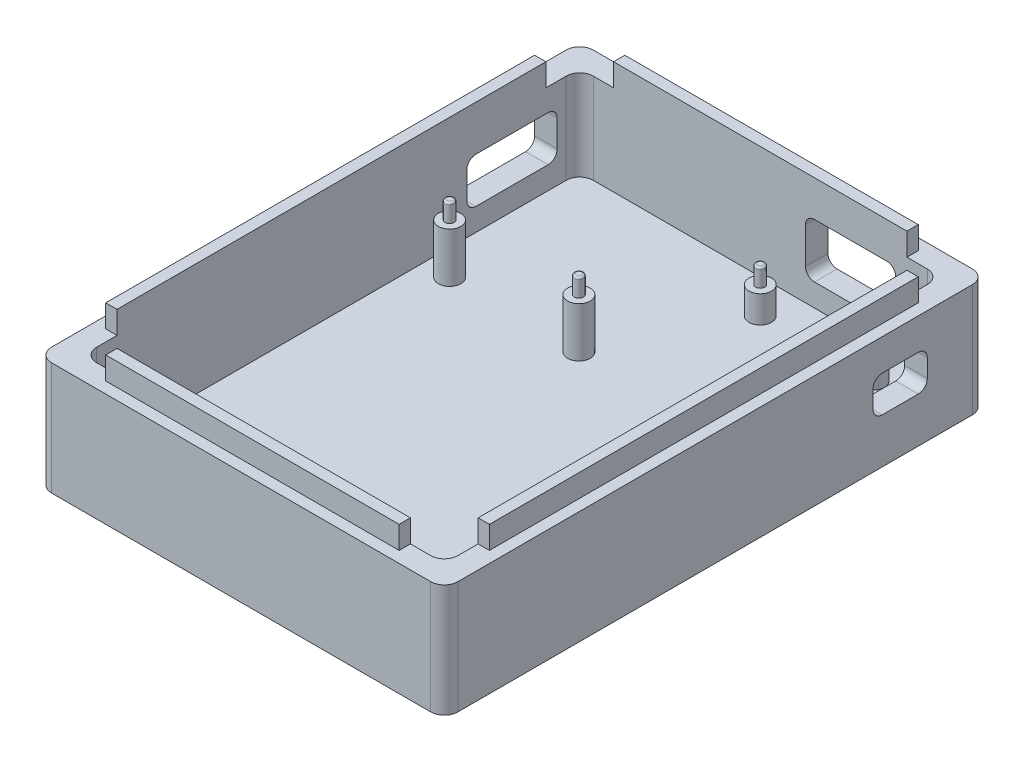
SolidWorks part; units mm, degrees
ref_plane "Alzado" through (0, 0, 0) normal (0, 0, 1) x (1, 0, 0)
ref_plane "Planta" through (0, 0, 0) normal (0, 1, 0) x (1, 0, 0)
ref_plane "Vista lateral" through (0, 0, 0) normal (1, 0, 0) x (0, 0, -1)
sketch "Croquis1" plane through (0, 0, 0) normal (0, 1, 0) x (1, 0, 0)
  line L1 (45, -60) -> (-45, -60)
  line L2 (45, -60) -> (45, 60)
  line L3 (45, 60) -> (-45, 60)
  line L4 (-45, -60) -> (-45, 60)
  line L5 (45, -60) -> (-45, 60) construction
  line L6 (45, 60) -> (-45, -60) construction
  point P0 (0, 0)
  dimension "D1" = 90
  dimension "D2" = 120
extrude "Saliente-Extruir1" add sketch "Croquis1" along normal blind 30
sketch "Croquis2" plane through (0, 30, 0) normal (0, 1, 0) x (1, 0, 0)
  line L0 (-45, 60) -> (-45, -60) construction
  line L1 (40, -55) -> (-40, -55)
  line L2 (40, -55) -> (40, 55)
  line L3 (40, 55) -> (-40, 55)
  line L4 (-40, -55) -> (-40, 55)
  line L5 (40, -55) -> (-40, 55) construction
  line L6 (40, 55) -> (-40, -55) construction
  line L7 (45, 60) -> (-45, 60) construction
  point P0 (0, 0)
  dimension "D1" = 5
  dimension "D2" = 5
extrude "Cortar-Extruir1" cut sketch "Croquis2" against normal blind 25
sketch "Croquis3" plane through (0, 30, 0) normal (0, 1, 0) x (1, 0, 0)
  line L1 (45, -60) -> (-45, -60)
  line L2 (45, -60) -> (45, 60)
  line L3 (45, 60) -> (-45, 60)
  line L4 (-45, -60) -> (-45, 60)
  line L5 (45, -60) -> (-45, 60) construction
  line L6 (45, 60) -> (-45, -60) construction
  line L7 (32.5, -57.5) -> (-32.5, -57.5)
  line L9 (32.5, 57.5) -> (-32.5, 57.5)
  line L11 (42.5, -57.5) -> (-42.5, 57.5) construction
  line L12 (42.5, 57.5) -> (-42.5, -57.5) construction
  line L15 (-42.5, 47.5) -> (-32.5, 47.5)
  line L16 (-32.5, 57.5) -> (-32.5, 47.5)
  line L17 (-42.5, 57.5) -> (-32.5, 47.5) construction
  line L18 (-42.5, 47.5) -> (-32.5, 57.5) construction
  line L19 (-42.5, -47.5) -> (-42.5, 47.5)
  line L22 (-42.5, -47.5) -> (-32.5, -47.5)
  line L23 (-32.5, -57.5) -> (-32.5, -47.5)
  line L24 (-42.5, -57.5) -> (-32.5, -47.5) construction
  line L25 (-42.5, -47.5) -> (-32.5, -57.5) construction
  line L29 (42.5, 47.5) -> (32.5, 47.5)
  line L30 (32.5, 57.5) -> (32.5, 47.5)
  line L31 (42.5, 57.5) -> (32.5, 47.5) construction
  line L32 (42.5, 47.5) -> (32.5, 57.5) construction
  line L33 (42.5, -47.5) -> (42.5, 47.5)
  line L36 (42.5, -47.5) -> (32.5, -47.5)
  line L37 (32.5, -57.5) -> (32.5, -47.5)
  line L38 (42.5, -57.5) -> (32.5, -47.5) construction
  line L39 (42.5, -47.5) -> (32.5, -57.5) construction
  point P0 (0, 0)
  point P5 (0, 0)
  point P15 (-37.5, 52.5)
  point P19 (-37.5, -52.5)
  point P23 (37.5, 52.5)
  point P27 (37.5, -52.5)
  dimension "D1" = 2.5
  dimension "D2" = 45
  dimension "D3" = 10
  dimension "D4" = 10
  dimension "D5" = 2.5
  dimension "D6" = 45
  dimension "D7" = 10
  dimension "D8" = 10
  dimension "D9" = 2.5
  dimension "D10" = 2.5
  dimension "D11" = 10
  dimension "D12" = 10
  dimension "D13" = 10
  dimension "D14" = 10
  dimension "D15" = 53.531
  dimension "D16" = 45
  dimension "D17" = 53.531
  dimension "D18" = 45
extrude "Cortar-Extruir2" cut sketch "Croquis3" against normal blind 5
sketch "Croquis4" plane through (0, 5, 0) normal (0, 1, 0) x (1, 0, 0)
  line L0 (0, 0) -> (-40, 0) construction
  line L1 (-40, 47.5) -> (-40, -47.5) construction
  line L2 (0, 0) -> (40, 0) construction
  line L3 (40, -47.5) -> (40, 47.5) construction
  line L4 (0, 0) -> (0, 55) construction
  line L5 (32.5, 55) -> (-32.5, 55) construction
  line L6 (0, 0) -> (0, -55) construction
  line L7 (-32.5, -55) -> (32.5, -55) construction
  line L8 (5.5, 49.5) -> (5.5, -49.5) construction
  line L9 (5.5, -49.5) -> (34.5, -49.5) construction
  line L10 (34.5, -49.5) -> (34.5, 49.5) construction
  line L11 (34.5, 49.5) -> (5.5, 49.5) construction
  line L12 (-40, -55) -> (40, -55) construction
  line L13 (40, 55) -> (-40, 55) construction
  line L14 (40, -55) -> (40, 55) construction
  line L15 (7.5, 49.5) -> (7.5, 47.5) construction
  line L16 (7.5, 47.5) -> (32.5, 47.5) construction
  line L17 (32.5, 47.5) -> (32.5, 49.5) construction
  line L18 (7.5, -49.5) -> (7.5, -47.5) construction
  line L19 (32.5, -47.5) -> (32.5, -49.5) construction
  line L20 (7.5, -47.5) -> (32.5, -47.5) construction
  circle A0 centre (7.5, 47.5) radius 2.5
  circle A1 centre (32.5, 47.5) radius 2.5
  circle A2 centre (32.5, -47.5) radius 2.5
  circle A3 centre (7.5, -47.5) radius 2.5
  dimension "D8" = 5
  dimension "D11" = 25
  dimension "D12" = 95
  dimension "D1" = 5.5
  dimension "D2" = 5.5
  dimension "D3" = 5.5
  dimension "D4" = 5.5
  dimension "D5" = 2
  dimension "D6" = 2
  dimension "D7" = 2
  dimension "D9" = 2
  dimension "D10" = 2
extrude "Saliente-Extruir2" add sketch "Croquis4" along normal blind 6
sketch "Croquis5" plane through (0, 11, 0) normal (0, 1, 0) x (1, 0, 0)
  circle A0 centre (7.5, 47.5) radius 1
  circle A1 centre (32.5, 47.5) radius 1
  circle A2 centre (32.5, -47.5) radius 1
  circle A3 centre (7.5, -47.5) radius 1
  circle A4 centre (7.5, -47.5) radius 2.5 construction
  dimension "D1" = 2
  dimension "D4" = 25
  dimension "D5" = 95
  dimension "D6" = 1.5
  dimension "D2" = 2
  dimension "D3" = 2
extrude "Saliente-Extruir3" add sketch "Croquis5" along normal blind 4
sketch "Croquis7" plane through (0, 5, 0) normal (0, 1, 0) x (1, 0, 0)
  line L0 (0, 0) -> (-40, 0) construction
  line L1 (0, 0) -> (40, 0) construction
  line L2 (0, 0) -> (0, 55) construction
  line L3 (0, 0) -> (0, -55) construction
  line L4 (40, -55) -> (40, 55) construction
  line L5 (40, 55) -> (-40, 55) construction
  line L6 (-40, -55) -> (40, -55) construction
  line L14 (-3.68, 22.5) -> (-3.68, -49.5) construction
  line L15 (-3.68, -49.5) -> (-36.32, -49.5) construction
  line L16 (-36.32, -49.5) -> (-36.32, 22.5) construction
  line L17 (-36.32, 22.5) -> (-3.68, 22.5) construction
  line L18 (-34.32, 22.5) -> (-34.32, 20.5) construction
  line L19 (-34.32, 20.5) -> (-5.68, 20.5) construction
  line L20 (-5.68, 20.5) -> (-5.68, 22.5) construction
  line L21 (-36.32, -13.5) -> (-3.68, -13.5) construction
  line L22 (-5.68, -47.5) -> (-5.68, -49.5) construction
  line L23 (-34.32, -49.5) -> (-34.32, -47.5) construction
  line L24 (-34.32, -47.5) -> (-5.68, -47.5) construction
  circle A4 centre (-34.32, 20.5) radius 2.5
  circle A5 centre (-5.68, 20.5) radius 2.5
  circle A6 centre (-5.68, -47.5) radius 2.5
  circle A7 centre (-34.32, -47.5) radius 2.5
  dimension "D4" = 5
  dimension "D11" = 5
  dimension "D12" = 5
  dimension "D13" = 5
  dimension "D14" = 28.64
  dimension "D15" = 68
  dimension "D1" = 32.64
  dimension "D2" = 3.68
  dimension "D3" = 2
  dimension "D5" = 2
  dimension "D6" = 72
  dimension "D7" = 40
  dimension "D8" = 55
  dimension "D9" = 28.64
  dimension "D10" = 5.5
extrude "Saliente-Extruir4" add sketch "Croquis7" along normal blind 11
sketch "Croquis8" plane through (0, 16, 0) normal (0, 1, 0) x (1, 0, 0)
  circle A0 centre (-34.32, 20.5) radius 1
  circle A1 centre (-5.68, 20.5) radius 1
  circle A2 centre (-5.68, -47.5) radius 1
  circle A3 centre (-34.32, -47.5) radius 1
  dimension "D1" = 2
  dimension "D2" = 2
extrude "Saliente-Extruir5" add sketch "Croquis8" along normal blind 4
sketch "Croquis10" plane through (0, 0, -60) normal (0, 0, -1) x (-1, 0, 0)
  line L1 (-30, 22) -> (-10, 22)
  line L2 (-30, 22) -> (-30, 10)
  line L3 (-30, 10) -> (-10, 10)
  line L4 (-10, 22) -> (-10, 10)
  line L5 (-30, 22) -> (-10, 10) construction
  line L6 (-30, 10) -> (-10, 22) construction
  line L7 (-45, 0) -> (45, 0) construction
  line L8 (-45, 25) -> (-45, 0) construction
  point P4 (-20, 16)
  dimension "D1" = 25
  dimension "D2" = 10
  dimension "D3" = 20
  dimension "D4" = 12
extrude "Cortar-Extruir3" cut sketch "Croquis10" against normal up to surface (5 mm away) up to face at (0, 21.25, -55)
sketch "Croquis11" plane through (45, 0, 0) normal (1, 0, 0) x (0, 0, -1)
  line L0 (60, 25) -> (60, 0) construction
  line L1 (35, 18) -> (47, 18)
  line L2 (35, 18) -> (35, 10)
  line L3 (35, 10) -> (47, 10)
  line L4 (47, 18) -> (47, 10)
  line L5 (35, 18) -> (47, 10) construction
  line L6 (35, 10) -> (47, 18) construction
  line L7 (-60, 0) -> (60, 0) construction
  point P4 (41, 14)
  dimension "D1" = 13
  dimension "D2" = 12
  dimension "D3" = 10
  dimension "D4" = 8
extrude "Cortar-Extruir4" cut sketch "Croquis11" against normal up to surface (5 mm away) up to face at (40, 21.25, 0)
sketch "Croquis12" plane through (-45, 0, 0) normal (-1, 0, 0) x (0, 0, 1)
  line L0 (-60, 0) -> (60, 0) construction
  line L1 (-50, 20) -> (-30, 20)
  line L2 (-50, 20) -> (-50, 10)
  line L3 (-50, 10) -> (-30, 10)
  line L4 (-30, 20) -> (-30, 10)
  line L5 (-50, 20) -> (-30, 10) construction
  line L6 (-50, 10) -> (-30, 20) construction
  line L7 (-60, 25) -> (-60, 0) construction
  point P4 (-40, 15)
  dimension "D1" = 10
  dimension "D2" = 10
  dimension "D3" = 10
  dimension "D4" = 20
extrude "Cortar-Extruir5" cut sketch "Croquis12" against normal up to surface (5 mm away) up to face at (-40, 21.25, 0)
fillet "Redondeo1" radius 3 4 edges at (-45, 12.5, 60) (45, 12.5, 60) (45, 12.5, -60) (-45, 12.5, -60)
fillet "Redondeo2" radius 2 12 edges at (-42.5, 20, -50) (-42.5, 10, -50) (-42.5, 20, -30) (-42.5, 10, -30) (30, 22, -57.5) (30, 10, -57.5) (10, 22, -57.5) (10, 10, -57.5) (42.5, 10, -35) (42.5, 18, -35) (42.5, 18, -47) (42.5, 10, -47)
fillet "Redondeo3" radius 3 4 edges at (-40, 15, 55) (40, 15, 55) (-40, 15, -55) (40, 15, -55)
fillet "Redondeo4" radius 0.4 8 edges at (7.5, 15, 48.5) (-34.32, 20, 48.5) (-5.68, 20, 48.5) (32.5, 15, 48.5) (-34.32, 20, -19.5) (-5.68, 20, -19.5) (32.5, 15, -46.5) (7.5, 15, -46.5)
